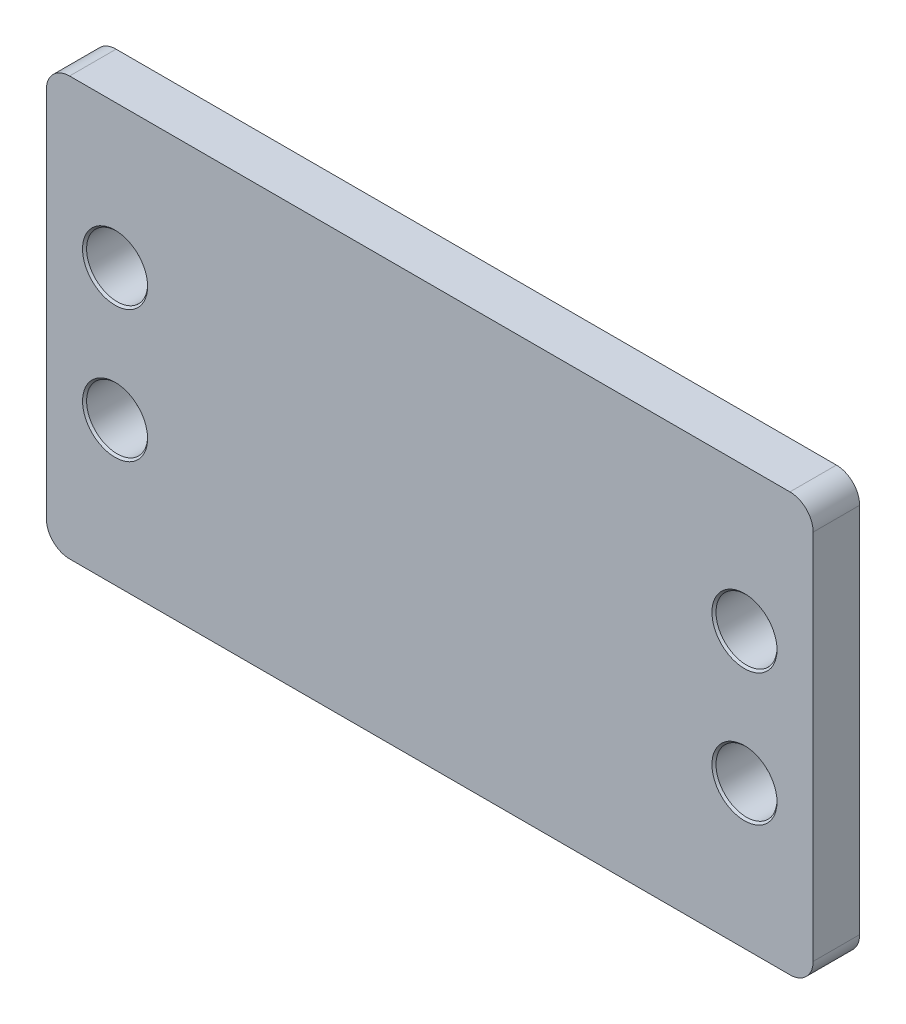
SolidWorks part; units mm, degrees
material "6061-T6 (SS)"
ref_plane "Front Plane" through (0, 0, 0) normal (0, 0, 1) x (1, 0, 0)
ref_plane "Top Plane" through (0, 0, 0) normal (0, 1, 0) x (1, 0, 0)
ref_plane "Right Plane" through (0, 0, 0) normal (1, 0, 0) x (0, 0, -1)
sketch "Sketch1" plane through (0, 0, 0) normal (0, 0, 1) x (1, 0, 0)
  line L1 (-52.3875, 28.575) -> (52.3875, 28.575)
  line L2 (-52.3875, 28.575) -> (-52.3875, -28.575)
  line L3 (-52.3875, -28.575) -> (52.3875, -28.575)
  line L4 (52.3875, 28.575) -> (52.3875, -28.575)
  point P4 (0, 28.575)
  point P5 (52.3875, 0)
  dimension "D1" = 104.775
  dimension "D2" = 57.15
extrude "Boss-Extrude1" add sketch "Sketch1" against normal blind 6.35
hole_wizard "21/64 (0.32813) Diameter Hole1" positions "Sketch3" profile "Sketch2" hole size "21/64" standard "Ansi Inch" end condition through all
sketch "Sketch3" plane through (0, 0, 0) normal (0, 0, 1) x (1, 0, 0)
  line L0 (52.3875, 28.575) -> (52.3875, -28.575) construction
  point P0 (43, 9)
  point P1 (43, -9)
  dimension "D1" = 9.3875
  dimension "D2" = 9
  dimension "D3" = 9
  dimension "D4" = 43
sketch "Sketch2" plane through (43, 9, 0) normal (1, 0, 0) x (0, -1, 0)
  line L0 (0, 0) -> (0, 6.35)
  line L1 (0, 6.35) -> (4.445, 6.35)
  line L2 (4.1673, 6.0723) -> (4.1673, 0.2777)
  line L3 (4.1673, 0.2777) -> (4.445, 0)
  line L5 (4.445, 0) -> (0, 0)
  line L6 (-4.1673, 0.2777) -> (-4.445, 0) construction
  line L7 (4.445, 6.35) -> (4.1673, 6.0723)
  line L8 (-4.445, 6.35) -> (-4.1673, 6.0723) construction
  line L11 (0, -6.35) -> (0, 107.95) construction
  dimension "Thru Hole Dia." = 8.3345
  dimension "Thru Hole Depth" = 6.35
  dimension "Near C'Sink Dia." = 8.89
  dimension "Near C'Sink Angle" = 90
  dimension "Far C'Sink Dia." = 8.89
  dimension "Far C'Sink Angle" = 90
mirror "Mirror1" about plane through (0, 0, 0) normal (1, 0, 0) of "21/64 (0.32813) Diameter Hole1"
fillet "Fillet1" radius 3.175 4 edges at (52.3875, 28.575, -3.175) (52.3875, -28.575, -3.175) (-52.3875, 28.575, -3.175) (-52.3875, -28.575, -3.175)
pattern_linear "LPattern1" [suppressed] count 2 spacing 228.6
